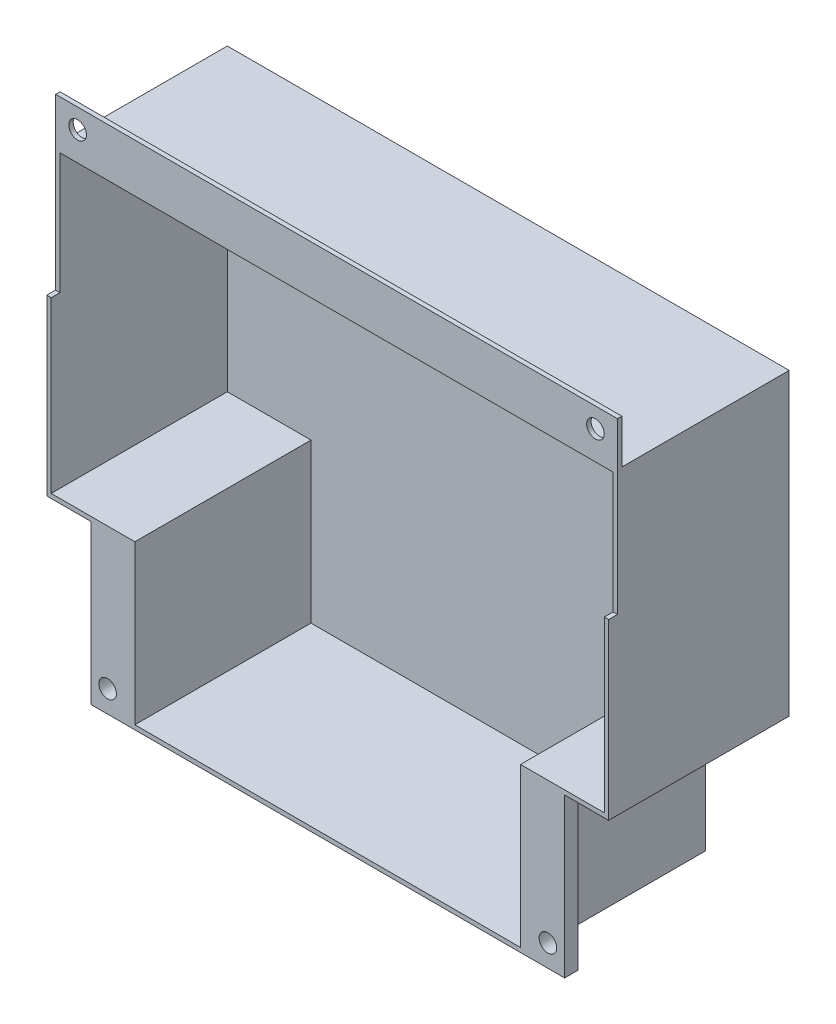
SolidWorks part; units mm, degrees
ref_plane "前视基准面" through (0, 0, 0) normal (0, 0, 1) x (1, 0, 0)
ref_plane "上视基准面" through (0, 0, 0) normal (0, 1, 0) x (1, 0, 0)
ref_plane "右视基准面" through (0, 0, 0) normal (1, 0, 0) x (0, 0, -1)
sketch "草图1" plane through (0, 0, 0) normal (0, 0, 1) x (1, 0, 0)
  line L0 (0, 0) -> (0, 104) construction
  line L1 (-63.8, 104) -> (63.8, 104)
  line L2 (63.8, 104) -> (63.8, 36)
  line L3 (63.8, 36) -> (44.8, 36)
  line L4 (44.8, 36) -> (44.8, 0)
  line L5 (44.8, 0) -> (-44.8, 0)
  line L6 (-44.8, 36) -> (-44.8, 0)
  line L7 (-63.8, 36) -> (-44.8, 36)
  line L8 (-63.8, 104) -> (-63.8, 36)
  dimension "D1" = 127.6
  dimension "D2" = 68
  dimension "D3" = 36
  dimension "D4" = 89.6
extrude "凸台-拉伸1" add sketch "草图1" along normal blind 1
sketch "草图2" plane through (0, 0, 1) normal (0, 0, 1) x (1, 0, 0)
  line L0 (62.8, 103) -> (-62.8, 103)
  line L1 (-62.8, 103) -> (-62.8, 37)
  line L2 (-62.8, 37) -> (-43.8, 37)
  line L3 (-43.8, 37) -> (-43.8, 1)
  line L4 (-43.8, 1) -> (43.8, 1)
  line L5 (43.8, 1) -> (43.8, 37)
  line L6 (43.8, 37) -> (62.8, 37)
  line L7 (62.8, 37) -> (62.8, 103)
  line L8 (-44.8, 36) -> (-44.8, 0)
  line L9 (-44.8, 0) -> (44.8, 0)
  line L10 (44.8, 0) -> (44.8, 36)
  line L11 (44.8, 36) -> (63.8, 36)
  line L12 (63.8, 36) -> (63.8, 104)
  line L13 (63.8, 104) -> (-63.8, 104)
  line L14 (-63.8, 104) -> (-63.8, 36)
  line L15 (-63.8, 36) -> (-44.8, 36)
  line L16 (-44.8, 36) -> (-44.8, 0)
  line L17 (-44.8, 0) -> (44.8, 0)
  line L18 (44.8, 0) -> (44.8, 36)
  line L19 (44.8, 36) -> (63.8, 36)
  line L20 (63.8, 36) -> (63.8, 104)
  line L21 (63.8, 104) -> (-63.8, 104)
  line L22 (-63.8, 104) -> (-63.8, 36)
  line L23 (-63.8, 36) -> (-44.8, 36)
  dimension "D1" = 0
  dimension "D2" = 1
extrude "凸台-拉伸2" add sketch "草图2" along normal blind 40
sketch "草图3" plane through (0, 0, 41) normal (0, 0, 1) x (1, 0, 0)
  line L1 (63.8, 104) -> (-63.8, 104)
  line L2 (63.8, 104) -> (63.8, 114)
  line L3 (63.8, 114) -> (-63.8, 114)
  line L4 (-63.8, 104) -> (-63.8, 114)
  line L5 (43.8, 37) -> (53.8, 37)
  line L6 (43.8, 37) -> (43.8, 0)
  line L7 (43.8, 0) -> (53.8, 0)
  line L8 (53.8, 37) -> (53.8, 0)
  line L9 (-43.8, 37) -> (-53.8, 37)
  line L10 (-43.8, 37) -> (-43.8, 0)
  line L11 (-43.8, 0) -> (-53.8, 0)
  line L12 (-53.8, 37) -> (-53.8, 0)
  line L13 (-63.8, 104) -> (-63.8, 36) construction
  line L14 (-44.8, 0) -> (44.8, 0) construction
  line L15 (0, 0) -> (0, 128.3164) construction
  circle A1 centre (58.8, 109.5) radius 2
  circle A2 centre (50, 5) radius 2
  circle A4 centre (-50, 5) radius 2
  circle A5 centre (-58.8, 109.5) radius 2
  dimension "D4" = 4
  dimension "D5" = 4
  dimension "D6" = 100
  dimension "D7" = 5
  dimension "D8" = 5
  dimension "D9" = 5.5
  dimension "D1" = 10
  dimension "D2" = 10
  dimension "D3" = 10
extrude "凸台-拉伸3" add sketch "草图3" against normal blind 3
sketch "草图4" plane through (-63.8, 0, 0) normal (-1, 0, 0) x (0, 0, 1)
  line L1 (41, 114) -> (39, 114)
  line L2 (41, 114) -> (41, 75.5)
  line L3 (41, 75.5) -> (39, 75.5)
  line L4 (39, 114) -> (39, 75.5)
  line L9 (38, 114) -> (38, 104) construction
  point P14 (0, 0)
  dimension "D1" = 1
  dimension "D3" = 38.5
extrude "切除-拉伸1" cut sketch "草图4" against normal through all
